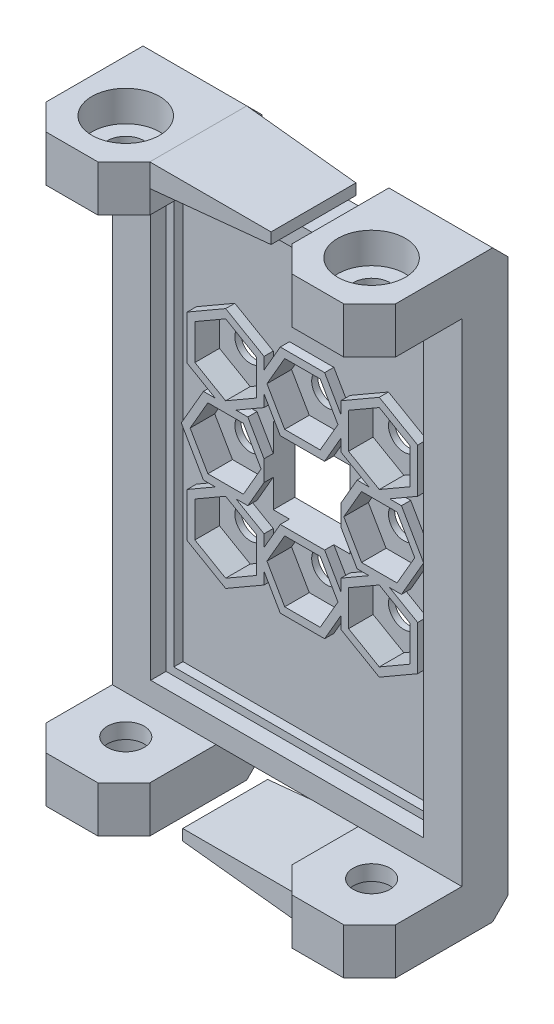
SolidWorks part; units mm, degrees
material "PE High Density"
ref_plane "Front Plane" through (0, 0, 0) normal (0, 0, 1) x (1, 0, 0)
ref_plane "Top Plane" through (0, 0, 0) normal (0, 1, 0) x (1, 0, 0)
ref_plane "Right Plane" through (0, 0, 0) normal (1, 0, 0) x (0, 0, -1)
sketch "Sketch1" plane through (0, 0, 0) normal (0, 0, 1) x (1, 0, 0)
  line L1 (-11.375, 19) -> (11.375, 19)
  line L2 (-11.375, 19) -> (-11.375, -19)
  line L3 (-11.375, -19) -> (11.375, -19)
  line L4 (11.375, 19) -> (11.375, -19)
  line L5 (-11.375, 19) -> (11.375, -19) construction
  line L6 (-11.375, -19) -> (11.375, 19) construction
  point P0 (0, 0)
  dimension "D1" = 22.75
  dimension "D2" = 38
extrude "Boss-Extrude1" add sketch "Sketch1" along normal blind 3
sketch "Sketch2" plane through (0, 0, 3) normal (0, 0, 1) x (1, 0, 0)
  line L0 (11.375, -19) -> (11.375, 19) construction
  line L1 (-11.375, 19) -> (11.375, 19)
  line L2 (-11.375, 19) -> (-11.375, 16)
  line L3 (-11.375, 16) -> (11.375, 16)
  line L4 (11.375, 19) -> (11.375, 16)
  line L6 (-11.375, -19) -> (11.375, -19)
  line L7 (-11.375, -19) -> (-11.375, -16)
  line L8 (-11.375, -16) -> (11.375, -16)
  line L9 (11.375, -19) -> (11.375, -16)
  dimension "D1" = 3
  dimension "D2" = 3
extrude "Boss-Extrude2" add sketch "Sketch2" along normal blind 6
sketch "Sketch4" plane through (0, 19, 0) normal (0, 1, 0) x (1, 0, 0)
  line L0 (11.375, -9) -> (-11.375, -9) construction
  line L1 (-4.625, -3) -> (4.625, -3)
  line L2 (-4.625, -3) -> (-4.625, -9)
  line L3 (-4.625, -9) -> (4.625, -9)
  line L4 (4.625, -3) -> (4.625, -9)
  line L5 (-4.625, -3) -> (4.625, -9) construction
  line L6 (-4.625, -9) -> (4.625, -3) construction
  line L7 (-11.375, -9) -> (-11.375, 0) construction
  line L8 (11.375, -9) -> (11.375, 0) construction
  point P0 (0, -6)
  dimension "D1" = 6.75
  dimension "D2" = 6.75
  dimension "D3" = 6
hole_wizard "CBORE for M2 SHCS1" positions "Sketch10" profile "Sketch11" counterbore size "M2" standard "Ansi Metric"
sketch "Sketch10" plane through (0, 19, 0) normal (0, 1, 0) x (-1, 0, 0)
  line L0 (11.375, 3) -> (-11.375, 3) construction
  line L1 (11.375, 9) -> (11.375, 0) construction
  line L2 (-11.375, 9) -> (-11.375, 0) construction
  point P0 (8, 5.5)
  point P1 (-8, 5.5)
  dimension "D1" = 2.5
  dimension "D2" = 2.5
  dimension "D3" = 3.375
  dimension "D4" = 3.375
sketch "Sketch11" plane through (-8, 19, 5.5) normal (1, 0, 0) x (0, 0, 1)
  line L0 (0, 0) -> (0, 3.721)
  line L1 (0, 3.721) -> (1.2, 3)
  line L2 (1.2, 3) -> (1.2, 2)
  line L3 (1.2, 2) -> (2.2, 2)
  line L4 (2.2, 2) -> (2.2, 0)
  line L5 (2.2, 0) -> (0, 0)
  line L10 (0, 3.721) -> (-1.2, 3) construction
  line L11 (0, -6.35) -> (0, 107.95) construction
  dimension "Hole Dia." = 2.4
  dimension "Hole Depth" = 3
  dimension "C'Bore Dia." = 4.4
  dimension "C'Bore Depth" = 2
  dimension "Drill Angle" = 118
extrude "Cut-Extrude5" cut sketch "Sketch4" against normal through all
hole_wizard "CBORE for M2 SHCS2" positions "Sketch14" profile "Sketch13" counterbore size "M2" standard "Ansi Metric" end condition through all
sketch "Sketch14" plane through (0, -19, 0) normal (0, -1, 0) x (1, 0, 0)
  point P0 (-8, 5.5)
  point P1 (8, 5.5)
sketch "Sketch13" plane through (-8, -19, 5.5) normal (1, 0, 0) x (0, 0, -1)
  line L0 (0, 0) -> (0, 38)
  line L1 (0, 38) -> (1.2, 38)
  line L3 (1.2, 38) -> (1.2, 2)
  line L4 (1.2, 2) -> (2.2, 2)
  line L5 (2.2, 2) -> (2.2, 0)
  line L7 (2.2, 0) -> (0, 0)
  line L11 (0, -6.35) -> (0, 107.95) construction
  dimension "Thru Hole Dia." = 2.4
  dimension "Thru Hole Depth" = 38
  dimension "C'Bore Dia." = 4.4
  dimension "C'Bore Depth" = 2
sketch "Sketch5" plane through (0, 0, 3) normal (0, 0, 1) x (1, 0, 0)
  line L1 (-8.875, -14.5) -> (8.875, -14.5)
  line L2 (-8.875, -14.5) -> (-8.875, 14.5)
  line L3 (-8.875, 14.5) -> (8.875, 14.5)
  line L4 (8.875, -14.5) -> (8.875, 14.5)
  line L5 (-8.875, -14.5) -> (8.875, 14.5) construction
  line L6 (-8.875, 14.5) -> (8.875, -14.5) construction
  line L8 (-11.375, 16) -> (-11.375, -16) construction
  point P0 (0, 0)
  dimension "D2" = 2.5
extrude "Cut-Extrude3" cut sketch "Sketch5" against normal blind 1
sketch "Sketch6" plane through (0, 0, 2) normal (0, 0, 1) x (1, 0, 0)
  line L0 (0, 14.5) -> (0, -14.5) construction
  line L1 (8.875, 14.5) -> (-8.875, 14.5) construction
  line L2 (-8.875, -14.5) -> (8.875, -14.5) construction
  line L3 (-8.875, 0) -> (8.875, 0) construction
  line L4 (-8.875, 14.5) -> (-8.875, -14.5) construction
  line L5 (8.875, -14.5) -> (8.875, 14.5) construction
  line L7 (-3, 3.8453) -> (-3, 6.1547)
  line L8 (-3, 6.1547) -> (-5, 7.3094)
  line L9 (-5, 7.3094) -> (-7, 6.1547)
  line L10 (-7, 6.1547) -> (-7, 3.8453)
  line L11 (-7, 3.8453) -> (-5, 2.6906)
  line L12 (-5, 2.6906) -> (-3, 3.8453)
  line L13 (1.1547, 3) -> (2.3094, 5)
  line L14 (2.3094, 5) -> (1.1547, 7)
  line L15 (1.1547, 7) -> (-1.1547, 7)
  line L16 (-1.1547, 7) -> (-2.3094, 5)
  line L17 (-2.3094, 5) -> (-1.1547, 3)
  line L18 (-1.1547, 3) -> (1.1547, 3)
  line L19 (5, 2.6906) -> (7, 3.8453)
  line L20 (7, 3.8453) -> (7, 6.1547)
  line L21 (7, 6.1547) -> (5, 7.3094)
  line L22 (5, 7.3094) -> (3, 6.1547)
  line L23 (3, 6.1547) -> (3, 3.8453)
  line L24 (3, 3.8453) -> (5, 2.6906)
  line L25 (-3.8453, -2) -> (-2.6906, 0)
  line L26 (-2.6906, 0) -> (-3.8453, 2)
  line L27 (-3.8453, 2) -> (-6.1547, 2)
  line L28 (-6.1547, 2) -> (-7.3094, 0)
  line L29 (-7.3094, 0) -> (-6.1547, -2)
  line L30 (-6.1547, -2) -> (-3.8453, -2)
  line L31 (0, -2.3094) -> (2, -1.1547)
  line L32 (2, -1.1547) -> (2, 1.1547)
  line L33 (2, 1.1547) -> (0, 2.3094)
  line L34 (0, 2.3094) -> (-2, 1.1547)
  line L35 (-2, 1.1547) -> (-2, -1.1547)
  line L36 (-2, -1.1547) -> (0, -2.3094)
  line L37 (7.3094, 0) -> (6.1547, 2)
  line L38 (6.1547, 2) -> (3.8453, 2)
  line L39 (3.8453, 2) -> (2.6906, 0)
  line L40 (2.6906, 0) -> (3.8453, -2)
  line L41 (3.8453, -2) -> (6.1547, -2)
  line L42 (6.1547, -2) -> (7.3094, 0)
  line L43 (-3, -6.1547) -> (-3, -3.8453)
  line L44 (-3, -3.8453) -> (-5, -2.6906)
  line L45 (-5, -2.6906) -> (-7, -3.8453)
  line L46 (-7, -3.8453) -> (-7, -6.1547)
  line L47 (-7, -6.1547) -> (-5, -7.3094)
  line L48 (-5, -7.3094) -> (-3, -6.1547)
  line L49 (1.1547, -7) -> (2.3094, -5)
  line L50 (2.3094, -5) -> (1.1547, -3)
  line L51 (1.1547, -3) -> (-1.1547, -3)
  line L52 (-1.1547, -3) -> (-2.3094, -5)
  line L53 (-2.3094, -5) -> (-1.1547, -7)
  line L54 (-1.1547, -7) -> (1.1547, -7)
  line L55 (5, -7.3094) -> (7, -6.1547)
  line L56 (7, -6.1547) -> (7, -3.8453)
  line L57 (7, -3.8453) -> (5, -2.6906)
  line L58 (5, -2.6906) -> (3, -3.8453)
  line L59 (3, -3.8453) -> (3, -6.1547)
  line L60 (3, -6.1547) -> (5, -7.3094)
  circle A0 centre (-5, 5) radius 2 construction
  circle A1 centre (0, 5) radius 2 construction
  circle A2 centre (5, 5) radius 2 construction
  circle A3 centre (-5, 0) radius 2 construction
  circle A4 centre (0, 0) radius 2 construction
  circle A5 centre (5, 0) radius 2 construction
  circle A6 centre (-5, -5) radius 2 construction
  circle A7 centre (0, -5) radius 2 construction
  circle A8 centre (5, -5) radius 2 construction
  dimension "D1" = 4
  dimension "D2" = 4
  dimension "D3" = 4
  dimension "D4" = 4
  dimension "D5" = 4
  dimension "D6" = 4
  dimension "D7" = 4
  dimension "D8" = 4
  dimension "D9" = 4
  dimension "D10" = 5
  dimension "D11" = 5
  dimension "D12" = 5
  dimension "D13" = 5
  dimension "D14" = 5
  dimension "D15" = 5
  dimension "D16" = 5
  dimension "D17" = 5
  dimension "D18" = 5
  dimension "D19" = 5
  dimension "D20" = 5
  dimension "D21" = 5
extrude "Cut-Extrude4" cut sketch "Sketch6" against normal blind 1.6
hole_wizard "Ø2.0 (2) Diameter Hole1" positions "Sketch8" profile "Sketch7" hole size "Ø2.0" standard "Ansi Metric"
sketch "Sketch8" plane through (0, 0, 0.4) normal (0, 0, 1) x (1, 0, 0)
  line L0 (-3, 6.1547) -> (-5, 7.3094) construction
  line L1 (-7, 6.1547) -> (-7, 3.8453) construction
  line L3 (2.3094, 5) -> (1.1547, 7) construction
  line L4 (-1.1547, 7) -> (-2.3094, 5) construction
  line L5 (7, 6.1547) -> (5, 7.3094) construction
  line L6 (3, 6.1547) -> (3, 3.8453) construction
  line L7 (2.3094, -5) -> (1.1547, -3) construction
  line L8 (-1.1547, -3) -> (-2.3094, -5) construction
  point P0 (-5, 5)
  point P1 (0, 5)
  point P3 (5, 5)
  point P5 (5, 0)
  point P7 (0, 0)
  point P10 (-5, 0)
  point P12 (-5, -5)
  point P14 (0, -5)
  point P16 (5, -5)
  point P21 (-4, 6.7321)
  point P24 (-7, 5)
  point P30 (1.7321, 6)
  point P33 (-1.7321, 6)
  point P36 (6, 6.7321)
  point P39 (3, 5)
  point P44 (1.7321, -4)
  point P47 (-1.7321, -4)
  dimension "D1" = 2
  dimension "D2" = 2
  dimension "D3" = 2
  dimension "D4" = 2
  dimension "D5" = 2
  dimension "D6" = 2
  dimension "D7" = 2
  dimension "D8" = 2
sketch "Sketch7" plane through (-5, 5, 0.4) normal (1, 0, 0) x (0, -1, 0)
  line L0 (0, 0) -> (0, 10.6009)
  line L1 (0, 10.6009) -> (1, 10)
  line L2 (1, 10) -> (1, 0)
  line L5 (1, 0) -> (0, 0)
  line L10 (0, 10.6009) -> (-1, 10) construction
  line L11 (0, -6.35) -> (0, 107.95) construction
  dimension "Hole Dia." = 2
  dimension "Hole Depth" = 10
  dimension "Drill Angle" = 118
sketch "Sketch15" plane through (0, 0, 2) normal (0, 0, 1) x (1, 0, 0)
  line L1 (-2.5, 2.5) -> (2.5, 2.5)
  line L2 (-2.5, 2.5) -> (-2.5, -2.5)
  line L3 (-2.5, -2.5) -> (2.5, -2.5)
  line L4 (2.5, 2.5) -> (2.5, -2.5)
  line L5 (-2.5, 2.5) -> (2.5, -2.5) construction
  line L6 (-2.5, -2.5) -> (2.5, 2.5) construction
  point P0 (0, 0)
  dimension "D1" = 5
  dimension "D2" = 5
extrude "Cut-Extrude6" cut sketch "Sketch15" against normal blind 10
sketch "Sketch16" plane through (0, 19, 0) normal (0, 1, 0) x (1, 0, 0)
  line L0 (-11.375, -7.312) -> (-9.6875, -9)
  line L1 (-11.375, -9) -> (-11.375, 0) construction
  line L2 (-4.625, -9) -> (-11.375, -9) construction
  line L3 (-4.625, -7.312) -> (-6.313, -9)
  line L4 (-4.625, -3) -> (-4.625, -9) construction
  line L5 (4.625, -7.312) -> (6.313, -9)
  line L6 (4.625, -9) -> (4.625, -3) construction
  line L7 (11.375, -9) -> (4.625, -9) construction
  line L8 (11.375, -7.312) -> (9.687, -9)
  line L9 (11.375, -9) -> (11.375, 0) construction
  line L10 (-2.436, 6.5807) -> (1.9128, 6.7863)
  line L11 (-11.375, -7.312) -> (-11.375, -9)
  line L12 (-11.375, -9) -> (-9.6875, -9)
  line L13 (-6.313, -9) -> (-4.625, -9)
  line L14 (-4.625, -9) -> (-4.625, -7.312)
  line L15 (4.625, -7.312) -> (4.625, -9)
  line L16 (4.625, -9) -> (6.313, -9)
  line L17 (9.687, -9) -> (11.375, -9)
  line L18 (11.375, -9) -> (11.375, -7.312)
  line M4 (4.625, -3) -> (4.625, -9)
  line M5 (4.625, -9) -> (11.375, -9)
  line M6 (11.375, -9) -> (11.375, 0)
  line M8 (-11.375, 0) -> (-11.375, -9)
  line M9 (-11.375, -9) -> (-4.625, -9)
  line M10 (-4.625, -9) -> (-4.625, -3)
  dimension "D1" = 1.6875
  dimension "D2" = 1.688
  dimension "D3" = 1.688
  dimension "D4" = 1.688
  dimension "D5" = 1.688
  dimension "D6" = 1.688
  dimension "D7" = 1.688
extrude "Cut-Extrude7" cut sketch "Sketch16" against normal through all contours L3 M10 M9 | L0 M8 M9 | L5 M4 M5 | L8 M6 M5
sketch "Sketch17" plane through (0, 0, 3) normal (0, 0, 1) x (1, 0, 0)
  line L0 (4.625, -19) -> (4.625, -16) construction
  line L1 (-4.625, 19) -> (4.625, 19)
  line L2 (-4.625, 19) -> (-4.625, 16)
  line L3 (-4.625, 16) -> (4.625, 16)
  line L4 (4.625, 19) -> (4.625, 16)
  line L5 (-4.625, -19) -> (4.625, -19)
  line L6 (-4.625, -19) -> (-4.625, -16)
  line L7 (-4.625, -16) -> (4.625, -16)
  line L8 (4.625, -19) -> (4.625, -16)
extrude "Cut-Extrude8" cut sketch "Sketch17" against normal blind 10
sketch "Sketch20" plane through (0, 0, 2) normal (0, 0, 1) x (1, 0, 0)
  line L0 (-4.3301, -2.5) -> (-3.5566, -2.5)
  line L1 (-2.5, 2.5) -> (-2.5, 0.6699)
  line L2 (-2.5, 2.5) -> (-2.5, -2.5) construction
  line L3 (-2.5, -2.5) -> (2.5, -2.5) construction
  line L4 (-2.5, -0.6699) -> (-2.5, -2.5)
  line L5 (-2.5, -2.5) -> (-1.4434, -2.5)
  line L6 (1.4434, -2.5) -> (2.5, -2.5)
  line L7 (2.5, -2.5) -> (2.5, -0.6699)
  line L8 (8.375, -14) -> (8.375, 14)
  line L9 (8.375, 14) -> (-8.375, 14)
  line L10 (-8.375, 14) -> (-8.375, -14)
  line L11 (-8.375, -14) -> (8.375, -14)
  line L12 (8.375, -14) -> (8.375, 14)
  line L13 (8.375, 14) -> (-8.375, 14)
  line L14 (-8.375, 14) -> (-8.375, -14)
  line L15 (-8.375, -14) -> (8.375, -14)
  line L16 (2.5, 0.6699) -> (2.5, 2.5)
  line L17 (2.5, 2.5) -> (1.4434, 2.5)
  line L18 (-1.4434, 2.5) -> (-2.5, 2.5)
  line L37 (2.8868, 5) -> (1.4434, 7.5)
  line L38 (1.4434, 2.5) -> (2.8868, 5)
  line L39 (-2.5, 3.5566) -> (-2.5, 6.4434)
  line L40 (-5, 2.1132) -> (-2.5, 3.5566)
  line L41 (-7.5, 3.5566) -> (-5, 2.1132)
  line L42 (-7.5, 6.4434) -> (-7.5, 3.5566)
  line L43 (-5, 7.8868) -> (-7.5, 6.4434)
  line L44 (-2.5, 6.4434) -> (-5, 7.8868)
  line L45 (-2.5, 3.5566) -> (-2.5, 4.3301)
  line L46 (-4.3301, 2.5) -> (-2.5, 3.5566)
  line L47 (-7.5, 3.5566) -> (-5.6699, 2.5)
  line L48 (-7.5, 6.4434) -> (-7.5, 3.5566)
  line L49 (-5, 7.8868) -> (-7.5, 6.4434)
  line L50 (-2.5, 6.4434) -> (-5, 7.8868)
  line L51 (-1.4434, 2.5) -> (1.4434, 2.5)
  line L52 (-2.8868, 5) -> (-1.4434, 2.5)
  line L53 (-1.4434, 7.5) -> (-2.8868, 5)
  line L54 (1.4434, 7.5) -> (-1.4434, 7.5)
  line L55 (2.5, 5.6699) -> (1.4434, 7.5)
  line L56 (1.4434, 2.5) -> (2.5, 4.3301)
  line L58 (-2.5, 4.3301) -> (-1.4434, 2.5)
  line L59 (-1.4434, 7.5) -> (-2.5, 5.6699)
  line L60 (1.4434, 7.5) -> (-1.4434, 7.5)
  line L82 (7.5, 3.5566) -> (7.5, 6.4434)
  line L83 (5, 2.1132) -> (7.5, 3.5566)
  line L84 (2.5, 3.5566) -> (5, 2.1132)
  line L85 (2.5, 6.4434) -> (2.5, 3.5566)
  line L86 (5, 7.8868) -> (2.5, 6.4434)
  line L87 (7.5, 6.4434) -> (5, 7.8868)
  line L88 (7.5, 3.5566) -> (7.5, 6.4434)
  line L89 (5.6699, 2.5) -> (7.5, 3.5566)
  line L90 (2.5, 3.5566) -> (4.3301, 2.5)
  line L91 (2.5, 6.4434) -> (2.5, 5.6699)
  line L92 (5, 7.8868) -> (2.5, 6.4434)
  line L93 (7.5, 6.4434) -> (5, 7.8868)
  line L115 (-2.1132, 0) -> (-3.5566, 2.5)
  line L116 (-3.5566, -2.5) -> (-2.1132, 0)
  line L117 (-6.4434, -2.5) -> (-3.5566, -2.5)
  line L118 (-7.8868, 0) -> (-6.4434, -2.5)
  line L119 (-6.4434, 2.5) -> (-7.8868, 0)
  line L120 (-3.5566, 2.5) -> (-6.4434, 2.5)
  line L121 (-2.5, 0.6699) -> (-3.5566, 2.5)
  line L122 (-3.5566, -2.5) -> (-2.5, -0.6699)
  line L123 (-6.4434, -2.5) -> (-5.6699, -2.5)
  line L124 (-7.8868, 0) -> (-6.4434, -2.5)
  line L125 (-6.4434, 2.5) -> (-7.8868, 0)
  line L126 (-3.5566, 2.5) -> (-4.3301, 2.5)
  line L148 (7.8868, 0) -> (6.4434, 2.5)
  line L149 (6.4434, -2.5) -> (7.8868, 0)
  line L150 (3.5566, -2.5) -> (6.4434, -2.5)
  line L151 (2.1132, 0) -> (3.5566, -2.5)
  line L152 (3.5566, 2.5) -> (2.1132, 0)
  line L153 (6.4434, 2.5) -> (3.5566, 2.5)
  line L154 (7.8868, 0) -> (6.4434, 2.5)
  line L155 (6.4434, -2.5) -> (7.8868, 0)
  line L156 (3.5566, -2.5) -> (4.3301, -2.5)
  line L157 (2.5, -0.6699) -> (3.5566, -2.5)
  line L158 (3.5566, 2.5) -> (2.5, 0.6699)
  line L159 (6.4434, 2.5) -> (5.6699, 2.5)
  line L181 (-2.5, -6.4434) -> (-2.5, -3.5566)
  line L182 (-5, -7.8868) -> (-2.5, -6.4434)
  line L183 (-7.5, -6.4434) -> (-5, -7.8868)
  line L184 (-7.5, -3.5566) -> (-7.5, -6.4434)
  line L185 (-5, -2.1132) -> (-7.5, -3.5566)
  line L186 (-2.5, -3.5566) -> (-5, -2.1132)
  line L187 (-2.5, -6.4434) -> (-2.5, -5.6699)
  line L188 (-5, -7.8868) -> (-2.5, -6.4434)
  line L189 (-7.5, -6.4434) -> (-5, -7.8868)
  line L190 (-7.5, -3.5566) -> (-7.5, -6.4434)
  line L191 (-5.6699, -2.5) -> (-7.5, -3.5566)
  line L192 (-2.5, -3.5566) -> (-4.3301, -2.5)
  line L214 (2.8868, -5) -> (1.4434, -2.5)
  line L215 (1.4434, -7.5) -> (2.8868, -5)
  line L216 (-1.4434, -7.5) -> (1.4434, -7.5)
  line L217 (-2.8868, -5) -> (-1.4434, -7.5)
  line L218 (-1.4434, -2.5) -> (-2.8868, -5)
  line L219 (1.4434, -2.5) -> (-1.4434, -2.5)
  line L220 (2.5, -4.3301) -> (1.4434, -2.5)
  line L221 (1.4434, -7.5) -> (2.5, -5.6699)
  line L222 (-1.4434, -7.5) -> (1.4434, -7.5)
  line L223 (-2.5, -5.6699) -> (-1.4434, -7.5)
  line L224 (-1.4434, -2.5) -> (-2.5, -4.3301)
  line L241 (-5.6699, 2.5) -> (-6.4434, 2.5)
  line L242 (-2.5, 5.6699) -> (-2.5, 6.4434)
  line L243 (2.5, 4.3301) -> (2.5, 3.5566)
  line L244 (4.3301, 2.5) -> (3.5566, 2.5)
  line L247 (7.5, -6.4434) -> (7.5, -3.5566)
  line L248 (5, -7.8868) -> (7.5, -6.4434)
  line L249 (2.5, -6.4434) -> (5, -7.8868)
  line L250 (2.5, -3.5566) -> (2.5, -6.4434)
  line L251 (5, -2.1132) -> (2.5, -3.5566)
  line L252 (7.5, -3.5566) -> (5, -2.1132)
  line L253 (7.5, -6.4434) -> (7.5, -3.5566)
  line L254 (5, -7.8868) -> (7.5, -6.4434)
  line L255 (2.5, -6.4434) -> (5, -7.8868)
  line L256 (2.5, -3.5566) -> (2.5, -4.3301)
  line L257 (4.3301, -2.5) -> (2.5, -3.5566)
  line L258 (7.5, -3.5566) -> (5.6699, -2.5)
  line L259 (5.6699, -2.5) -> (6.4434, -2.5)
  line L260 (2.5, -5.6699) -> (2.5, -6.4434)
  line L261 (-2.5, -4.3301) -> (-2.5, -3.5566)
  dimension "D1" = 0.5
  dimension "D2" = 0.5
  dimension "D3" = 0.5
  dimension "D4" = 0.5
  dimension "D5" = 0.5
  dimension "D6" = 0.5
  dimension "D7" = 0.5
  dimension "D8" = 0.5
  dimension "D9" = 0.5
extrude "Cut-Extrude9" cut sketch "Sketch20" against normal blind 0.6 contours L14 L15 L12 L13 L260 L221 L222 L223 L187 L188 L189 L190 L191 L123 L124 L125 L241 L47 L48 L49 L50 L242 L59 L60 L55 L91 L92 L93 L88 L89 L159 L154 L155 L259 L258 L253 L254 L255 | L126 L121 L1 L18 L58 L45 L46 | L244 L90 L243 L56 L17 L16 L158 | L257 L156 L157 L7 L6 L220 L256 | L261 L224 L5 L4 L122 L0 L192
chamfer "Chamfer1" distance 1 angle 45 4 edges at (-8, -19, 0) (8, -19, 0) (-8, 19, 0) (8, 19, 0)
sketch "Sketch21" plane through (4.625, 0, 0) normal (-1, 0, 0) x (0, 0, 1)
  line L0 (7.312, -19) -> (7.312, -16) construction
  line L1 (1, -19) -> (7.312, -19)
  line L2 (1, -19) -> (1, -17.5)
  line L3 (1, -17.5) -> (7.312, -17.5)
  line L4 (7.312, -19) -> (7.312, -17.5)
extrude "Boss-Extrude3" add sketch "Sketch21" along normal blind 7.5 draft 3
sketch "Sketch22" plane through (-4.625, 0, 0) normal (1, 0, 0) x (0, 0, -1)
  line L0 (-7.312, 19) -> (-7.312, 16) construction
  line L1 (-1, 19) -> (-7.312, 19)
  line L2 (-1, 19) -> (-1, 17.5)
  line L3 (-1, 17.5) -> (-7.312, 17.5)
  line L4 (-7.312, 19) -> (-7.312, 17.5)
extrude "Boss-Extrude4" add sketch "Sketch22" along normal blind 7.5 draft 3
